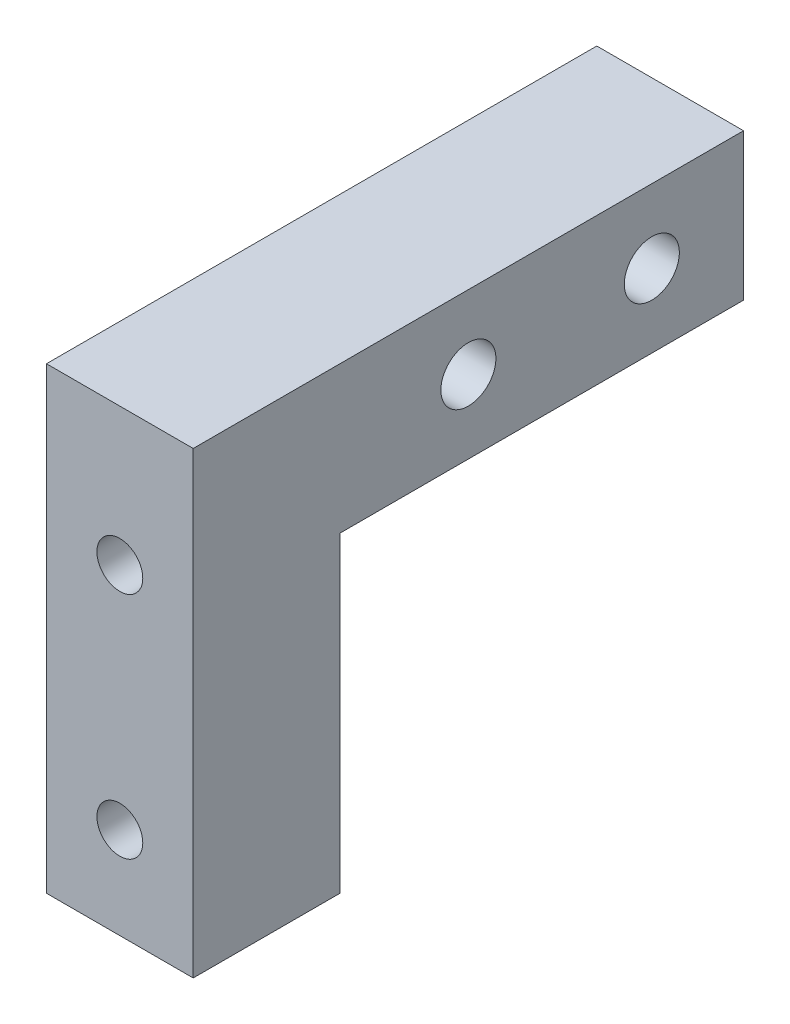
SolidWorks part; units mm, degrees
material "1060 Alloy"
ref_plane "Front Plane" through (0, 0, 0) normal (0, 0, 1) x (1, 0, 0)
ref_plane "Top Plane" through (0, 0, 0) normal (0, 1, 0) x (1, 0, 0)
ref_plane "Right Plane" through (0, 0, 0) normal (1, 0, 0) x (0, 0, -1)
sketch "Sketch1" plane through (0, 0, 0) normal (1, 0, 0) x (0, 0, -1)
  line L0 (0, 0) -> (0, -34)
  line L1 (0, -34) -> (-16, -34)
  line L2 (-16, -34) -> (-16, 16)
  line L3 (-16, 16) -> (44, 16)
  line L4 (44, 16) -> (44, 0)
  line L5 (44, 0) -> (0, 0)
  dimension "D1" = 16
  dimension "D2" = 16
  dimension "D3" = 50
  dimension "D4" = 60
extrude "Boss-Extrude1" add sketch "Sketch1" along normal mid plane 16
sketch "Sketch2" plane through (-8, 0, 0) normal (-1, 0, 0) x (0, 0, 1)
  line L0 (-44, 8) -> (23.8806, 8) construction
  line L1 (-44, 0) -> (-44, 16) construction
  line L2 (-44, 16) -> (16, 16) construction
  circle A0 centre (-34, 8) radius 3
  circle A1 centre (-14, 8) radius 3
  dimension "D2" = 6
  dimension "D3" = 6
  dimension "D4" = 10
  dimension "D5" = 20
  dimension "D1" = 8
extrude "Cut-Extrude1" cut sketch "Sketch2" against normal through all
sketch "Sketch5" plane through (0, 0, 16) normal (0, 0, 1) x (1, 0, 0)
  line L0 (0, 17.0028) -> (0, -35.3238) construction
  line L1 (8, 16) -> (-8, 16) construction
  point P3 (0, 1)
  point P4 (0, -24)
  dimension "D1" = 15
  dimension "D2" = 25
hole_wizard "Ø5.0 (5) Diameter Hole2" positions "3DSketch2" profile "Sketch10" hole size "Ø5.0" standard "ANSI Metric"
sketch3d "3DSketch2"
  point P0 (0, 1, 16)
  point P3 (0, -24, 16)
sketch "Sketch10" plane through (0, 1, 16) normal (1, 0, 0) x (0, -1, 0)
  line L0 (0, 0) -> (0, 13.5022)
  line L1 (0, 13.5022) -> (2.5, 12)
  line L2 (2.5, 12) -> (2.5, 0)
  line L5 (2.5, 0) -> (0, 0)
  line L10 (0, 13.5022) -> (-2.5, 12) construction
  line L11 (0, -6.35) -> (0, 107.95) construction
  dimension "Hole Dia." = 5
  dimension "Hole Depth" = 12
  dimension "Drill Angle" = 118
cosmetic thread "Cosmetic Thread4" parameters "D1"=10, "D2"=6
cosmetic thread "Cosmetic Thread5" parameters "D1"=10, "D2"=6
